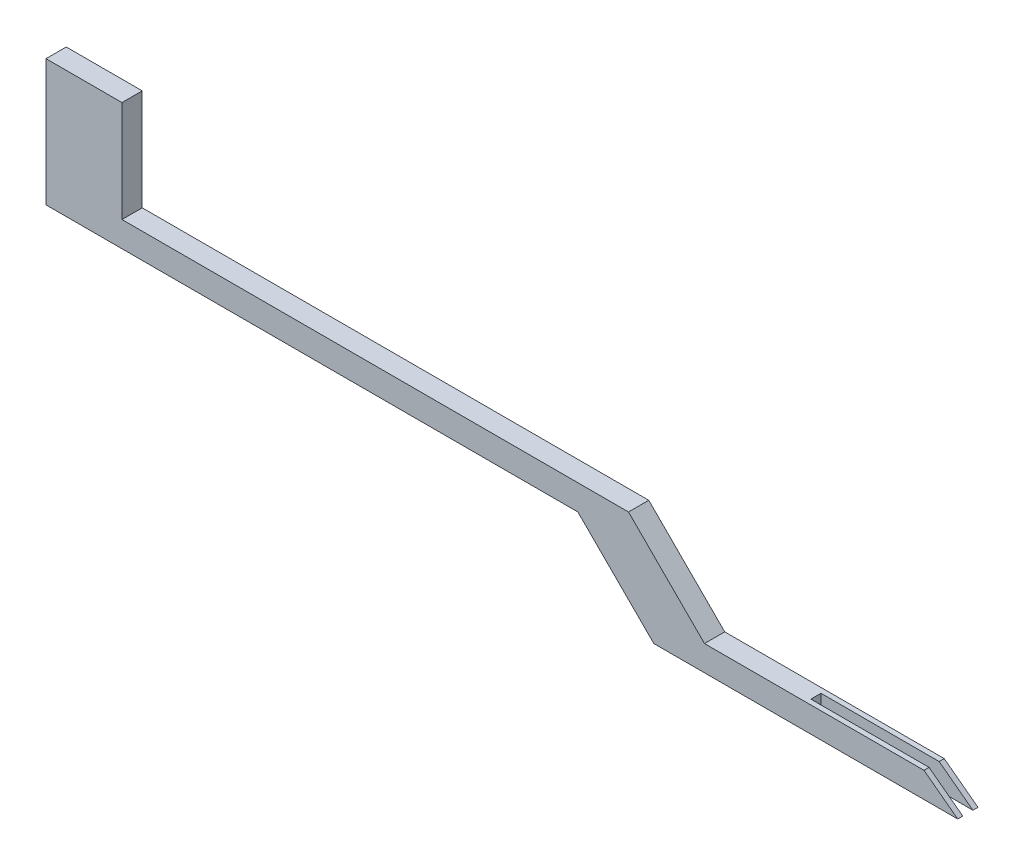
SolidWorks part; units mm, degrees
ref_plane "Ön Düzlem" through (0, 0, 0) normal (0, 0, 1) x (1, 0, 0)
ref_plane "Üst Düzlem" through (0, 0, 0) normal (0, 1, 0) x (1, 0, 0)
ref_plane "Sağ Düzlem" through (0, 0, 0) normal (1, 0, 0) x (0, 0, -1)
sketch "Sketch3" plane through (0, 0, 0) normal (0, 0, 1) x (1, 0, 0)
  line L0 (0, 0) -> (0, 2.5)
  line L1 (0, 2.5) -> (1.5, 2.5)
  line L2 (1.5, 2.5) -> (1.5, 0.5)
  line L3 (1.5, 0.5) -> (11.5, 0.5)
  line L4 (11.5, 0.5) -> (13, -1)
  line L5 (13, -1) -> (17.3333, -1)
  line L6 (17.3333, -1) -> (18, -1.5)
  line L7 (18, -1.5) -> (12, -1.5)
  line L8 (12, -1.5) -> (10.5, 0)
  line L9 (10.5, 0) -> (0, 0)
  point P3 (11.7969, 0.5)
  dimension "D1" = 1.5
  dimension "D2" = 2.5
  dimension "D3" = 0.5
  dimension "D4" = 10.5
  dimension "D5" = 1
  dimension "D6" = 1
  dimension "D7" = 135
  dimension "D8" = 6
  dimension "D9" = 1.5
  dimension "D10" = 0.5
  dimension "D11" = 0.6667
extrude "Boss-Extrude1" add sketch "Sketch3" along normal blind 0.4
sketch "Sketch5" plane through (0, -1, 0) normal (0, 1, 0) x (1, 0, 0)
  line L0 (18, -0.4) -> (18, 0) construction
  line L1 (18, -0.1) -> (15, -0.1)
  line L2 (18, -0.1) -> (18, -0.3)
  line L3 (18, -0.3) -> (15, -0.3)
  line L4 (15, -0.1) -> (15, -0.3)
  line L5 (17.3333, -0.4) -> (13, -0.4) construction
  dimension "D1" = 0.2
  dimension "D2" = 0.1
  dimension "D3" = 3
extrude "Cut-Extrude1" cut sketch "Sketch5" against normal blind 0.7
